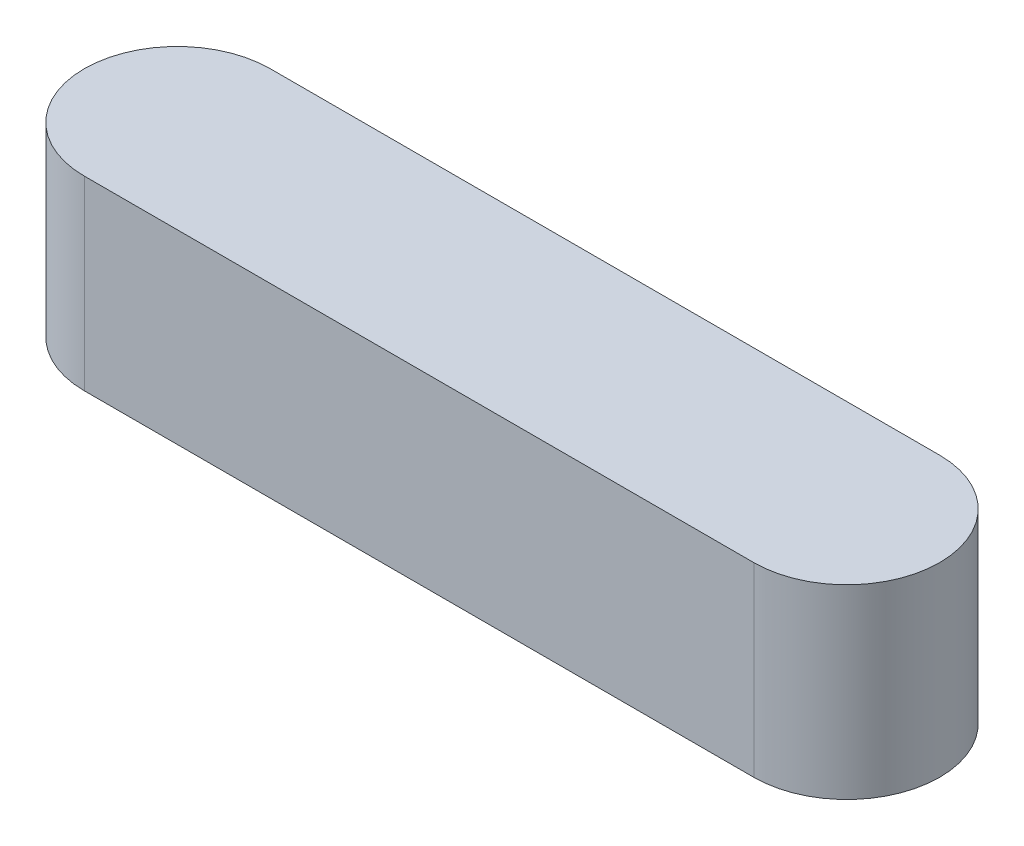
SolidWorks part; units mm, degrees
material "1.4401 (X5CrNiMo17-12-2)"
ref_plane "正面" through (0, 0, 0) normal (0, 0, 1) x (1, 0, 0)
ref_plane "平面" through (0, 0, 0) normal (0, 1, 0) x (1, 0, 0)
ref_plane "右側面" through (0, 0, 0) normal (1, 0, 0) x (0, 0, -1)
sketch "ｽｹｯﾁ1" plane through (0, 0, 0) normal (0, 1, 0) x (1, 0, 0)
  line L0 (-9, 0) -> (9, 0) construction
  line L1 (-9, 2.5) -> (9, 2.5)
  line L2 (-9, -2.5) -> (9, -2.5)
  arc A0 (-9, 2.5) -> (-9, -2.5) centre (-9, 0) ccw
  arc A1 (9, -2.5) -> (9, 2.5) centre (9, 0) ccw
  point P2 (0, 0)
  dimension "D2" = 23
  dimension "D1" = 5
extrude "ﾎﾞｽ - 押し出し1" add sketch "ｽｹｯﾁ1" along normal mid plane 5
